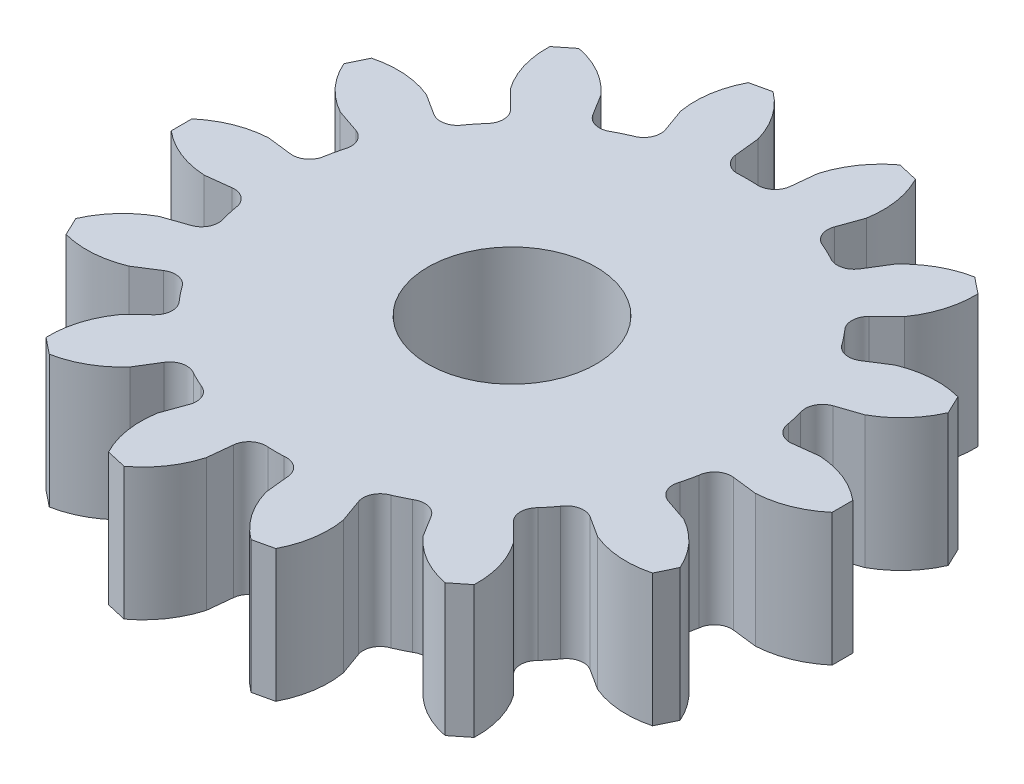
SolidWorks part; units mm, degrees
material "PLA"
ref_plane "Front Plane" through (0, 0, 0) normal (0, 0, 1) x (1, 0, 0)
ref_plane "Top Plane" through (0, 0, 0) normal (0, 1, 0) x (1, 0, 0)
ref_plane "Right Plane" through (0, 0, 0) normal (1, 0, 0) x (0, 0, -1)
sketch "Sketch1" plane through (0, 0, 0) normal (0, 1, 0) x (1, 0, 0)
  line L0 (0, 0) -> (-9.9867, 0) construction
  line L1 (-7.9271, 2.7354) -> (-7.213, 2.4916)
  line L2 (-9.1335, 4.0511) -> (-8.8619, 4.615)
  line L3 (-7.0811, 4.4922) -> (-6.4452, 4.0858)
  line L4 (-5.9552, 5.904) -> (-5.4176, 5.3745)
  line L5 (-6.4713, 7.6128) -> (-5.9819, 8.0031)
  line L6 (-4.4308, 7.1197) -> (-4.0342, 6.4777)
  line L7 (-2.8038, 7.9032) -> (-2.5492, 7.1928)
  line L8 (-2.5274, 9.6667) -> (-1.9171, 9.806)
  line L9 (-0.9029, 8.3371) -> (-0.8241, 7.5866)
  line L10 (0.9029, 8.3371) -> (0.8241, 7.5866)
  line L11 (1.9171, 9.806) -> (2.5274, 9.6667)
  line L12 (2.8038, 7.9032) -> (2.5492, 7.1928)
  line L13 (4.4308, 7.1197) -> (4.0342, 6.4777)
  line L14 (5.9819, 8.0031) -> (6.4713, 7.6128)
  line L15 (5.9552, 5.904) -> (5.4176, 5.3745)
  line L16 (7.0811, 4.4922) -> (6.4452, 4.0858)
  line L17 (-9.9867, -0.313) -> (-9.9867, 0.313)
  line L18 (-9.9867, 0.313) -> (-8.9385, 0.313) construction
  line L19 (-8.9385, 0.313) -> (-8.9385, 0.8733) construction
  line L20 (-8.9385, 0.8733) -> (-8.3289, 0.8733) construction
  line L21 (-8.3289, 0.8733) -> (-8.3289, 0.9749) construction
  line L22 (-8.3289, 0.9749) -> (-7.5797, 0.9749) construction
  line L23 (-7.5797, 0.9749) -> (-7.5797, 0.8847) construction
  line L24 (-8.3289, 0.9749) -> (-7.5797, 0.8847)
  line L25 (-7.5797, 0.8847) -> (-7.5797, 1.3491) construction
  line L26 (-7.5797, 1.3491) -> (-7.0037, 1.3491) construction
  line L27 (-8.3289, -0.9749) -> (-7.5797, -0.8847)
  line L28 (8.8619, 4.615) -> (9.1335, 4.0511)
  line L29 (7.9271, 2.7354) -> (7.213, 2.4916)
  line L30 (8.3289, 0.9749) -> (7.5797, 0.8847)
  line L31 (9.9867, 0.313) -> (9.9867, -0.313)
  line L32 (8.3289, -0.9749) -> (7.5797, -0.8847)
  line L33 (7.9271, -2.7354) -> (7.213, -2.4916)
  line L34 (9.1335, -4.0511) -> (8.8619, -4.615)
  line L35 (7.0811, -4.4922) -> (6.4452, -4.0858)
  line L36 (5.9552, -5.904) -> (5.4176, -5.3745)
  line L37 (6.4713, -7.6128) -> (5.9819, -8.0031)
  line L38 (4.4308, -7.1197) -> (4.0342, -6.4777)
  line L39 (2.8038, -7.9032) -> (2.5492, -7.1928)
  line L40 (2.5274, -9.6667) -> (1.9171, -9.806)
  line L41 (0.9029, -8.3371) -> (0.8241, -7.5866)
  line L42 (-0.9029, -8.3371) -> (-0.8241, -7.5866)
  line L43 (-1.9171, -9.806) -> (-2.5274, -9.6667)
  line L44 (-2.8038, -7.9032) -> (-2.5492, -7.1928)
  line L45 (-4.4308, -7.1197) -> (-4.0342, -6.4777)
  line L46 (-5.9819, -8.0031) -> (-6.4713, -7.6128)
  line L47 (-5.9552, -5.904) -> (-5.4176, -5.3745)
  line L48 (-7.0811, -4.4922) -> (-6.4452, -4.0858)
  line L49 (-8.8619, -4.615) -> (-9.1335, -4.0511)
  line L50 (-7.9271, -2.7354) -> (-7.213, -2.4916)
  line L51 (0, 0) -> (0, 2.54) construction
  arc A122 (-7.0037, -1.3491) -> (-6.8955, -1.8233) centre (0, 0) ccw
  arc A123 (-6.8955, 1.8233) -> (-7.0037, 1.3491) centre (0, 0) ccw
  arc A124 (-7.213, 2.4916) -> (-6.8955, 1.8233) centre (-7.3799, 2.0028) cw
  arc A125 (-9.9867, 0.313) -> (-8.3289, 0.9749) centre (-8.1781, -1.8096) cw
  arc A126 (-7.5797, 0.8847) -> (-7.0037, 1.3491) centre (-7.518, 1.3976) ccw
  arc A127 (-9.1335, 4.0511) -> (-7.9271, 2.7354) centre (-6.5831, 5.1788) ccw
  arc A128 (-7.5797, -0.8847) -> (-7.0037, -1.3491) centre (-7.518, -1.3976) cw
  arc A129 (-9.9867, -0.313) -> (-8.3289, -0.9749) centre (-8.1781, 1.8096) ccw
  arc A130 (-8.8619, 4.615) -> (-7.0811, 4.4922) centre (-8.1534, 1.9179) cw
  arc A131 (-6.4452, 4.0858) -> (-5.7248, 4.2543) centre (-6.1671, 4.5211) ccw
  arc A132 (-5.4215, 4.6346) -> (-5.7248, 4.2543) centre (0, 0) ccw
  arc A133 (-5.4176, 5.3745) -> (-5.4215, 4.6346) centre (-5.78, 5.0065) cw
  arc A134 (-6.4713, 7.6128) -> (-5.9552, 5.904) centre (-3.6842, 7.5222) ccw
  arc A135 (-5.9819, 8.0031) -> (-4.4308, 7.1197) centre (-6.5138, 5.2656) cw
  arc A136 (-4.0342, 6.4777) -> (-3.312, 6.3169) centre (-3.5947, 6.7492) ccw
  arc A137 (-2.8738, 6.5279) -> (-3.312, 6.3169) centre (0, 0) ccw
  arc A138 (-2.5492, 7.1928) -> (-2.8738, 6.5279) centre (-3.0354, 7.0185) cw
  arc A139 (-2.5274, 9.6667) -> (-2.8038, 7.9032) centre (-0.0556, 8.3758) ccw
  arc A140 (-1.9171, 9.806) -> (-0.9029, 8.3371) centre (-3.584, 7.5704) cw
  arc A141 (-0.8241, 7.5866) -> (-0.2432, 7.1284) centre (-0.3104, 7.6405) ccw
  arc A142 (0.2432, 7.1284) -> (-0.2432, 7.1284) centre (0, 0) ccw
  arc A143 (0.8241, 7.5866) -> (0.2432, 7.1284) centre (0.3104, 7.6405) cw
  arc A144 (1.9171, 9.806) -> (0.9029, 8.3371) centre (3.584, 7.5704) ccw
  arc A145 (2.5274, 9.6667) -> (2.8038, 7.9032) centre (0.0556, 8.3758) cw
  arc A146 (2.5492, 7.1928) -> (2.8738, 6.5279) centre (3.0354, 7.0185) ccw
  arc A147 (3.312, 6.3169) -> (2.8738, 6.5279) centre (0, 0) ccw
  arc A148 (4.0342, 6.4777) -> (3.312, 6.3169) centre (3.5947, 6.7492) cw
  arc A149 (5.9819, 8.0031) -> (4.4308, 7.1197) centre (6.5138, 5.2656) ccw
  arc A150 (6.4713, 7.6128) -> (5.9552, 5.904) centre (3.6842, 7.5222) cw
  arc A151 (5.4176, 5.3745) -> (5.4215, 4.6346) centre (5.78, 5.0065) ccw
  arc A152 (5.7248, 4.2543) -> (5.4215, 4.6346) centre (0, 0) ccw
  arc A153 (6.4452, 4.0858) -> (5.7248, 4.2543) centre (6.1671, 4.5211) cw
  arc A154 (8.8619, 4.615) -> (7.0811, 4.4922) centre (8.1534, 1.9179) ccw
  arc A155 (9.1335, 4.0511) -> (7.9271, 2.7354) centre (6.5831, 5.1788) cw
  arc A156 (7.213, 2.4916) -> (6.8955, 1.8233) centre (7.3799, 2.0028) ccw
  arc A157 (7.0037, 1.3491) -> (6.8955, 1.8233) centre (0, 0) ccw
  arc A158 (7.5797, 0.8847) -> (7.0037, 1.3491) centre (7.518, 1.3976) cw
  arc A159 (9.9867, 0.313) -> (8.3289, 0.9749) centre (8.1781, -1.8096) ccw
  arc A160 (9.9867, -0.313) -> (8.3289, -0.9749) centre (8.1781, 1.8096) cw
  arc A161 (7.5797, -0.8847) -> (7.0037, -1.3491) centre (7.518, -1.3976) ccw
  arc A162 (6.8955, -1.8233) -> (7.0037, -1.3491) centre (0, 0) ccw
  arc A163 (7.213, -2.4916) -> (6.8955, -1.8233) centre (7.3799, -2.0028) cw
  arc A164 (9.1335, -4.0511) -> (7.9271, -2.7354) centre (6.5831, -5.1788) ccw
  arc A165 (8.8619, -4.615) -> (7.0811, -4.4922) centre (8.1534, -1.9179) cw
  arc A166 (6.4452, -4.0858) -> (5.7248, -4.2543) centre (6.1671, -4.5211) ccw
  arc A167 (5.4215, -4.6346) -> (5.7248, -4.2543) centre (0, 0) ccw
  arc A168 (5.4176, -5.3745) -> (5.4215, -4.6346) centre (5.78, -5.0065) cw
  arc A169 (6.4713, -7.6128) -> (5.9552, -5.904) centre (3.6842, -7.5222) ccw
  arc A170 (5.9819, -8.0031) -> (4.4308, -7.1197) centre (6.5138, -5.2656) cw
  arc A171 (4.0342, -6.4777) -> (3.312, -6.3169) centre (3.5947, -6.7492) ccw
  arc A172 (2.8738, -6.5279) -> (3.312, -6.3169) centre (0, 0) ccw
  arc A173 (2.5492, -7.1928) -> (2.8738, -6.5279) centre (3.0354, -7.0185) cw
  arc A174 (2.5274, -9.6667) -> (2.8038, -7.9032) centre (0.0556, -8.3758) ccw
  arc A175 (1.9171, -9.806) -> (0.9029, -8.3371) centre (3.584, -7.5704) cw
  arc A176 (0.8241, -7.5866) -> (0.2432, -7.1284) centre (0.3104, -7.6405) ccw
  arc A177 (-0.2432, -7.1284) -> (0.2432, -7.1284) centre (0, 0) ccw
  arc A178 (-0.8241, -7.5866) -> (-0.2432, -7.1284) centre (-0.3104, -7.6405) cw
  arc A179 (-1.9171, -9.806) -> (-0.9029, -8.3371) centre (-3.584, -7.5704) ccw
  arc A180 (-2.5274, -9.6667) -> (-2.8038, -7.9032) centre (-0.0556, -8.3758) cw
  arc A181 (-2.5492, -7.1928) -> (-2.8738, -6.5279) centre (-3.0354, -7.0185) ccw
  arc A182 (-3.312, -6.3169) -> (-2.8738, -6.5279) centre (0, 0) ccw
  arc A183 (-4.0342, -6.4777) -> (-3.312, -6.3169) centre (-3.5947, -6.7492) cw
  arc A184 (-5.9819, -8.0031) -> (-4.4308, -7.1197) centre (-6.5138, -5.2656) ccw
  arc A185 (-6.4713, -7.6128) -> (-5.9552, -5.904) centre (-3.6842, -7.5222) cw
  arc A186 (-5.4176, -5.3745) -> (-5.4215, -4.6346) centre (-5.78, -5.0065) ccw
  arc A187 (-5.7248, -4.2543) -> (-5.4215, -4.6346) centre (0, 0) ccw
  arc A188 (-6.4452, -4.0858) -> (-5.7248, -4.2543) centre (-6.1671, -4.5211) cw
  arc A189 (-8.8619, -4.615) -> (-7.0811, -4.4922) centre (-8.1534, -1.9179) ccw
  arc A190 (-9.1335, -4.0511) -> (-7.9271, -2.7354) centre (-6.5831, -5.1788) cw
  arc A191 (-7.213, -2.4916) -> (-6.8955, -1.8233) centre (-7.3799, -2.0028) ccw
  circle A194 centre (0, 0) radius 2.5424
  point P99 (-9.9911, 0)
  dimension "D20" = 0.5603
  dimension "D21" = 1.0482
  dimension "D22" = 0.1016
  dimension "D23" = 0.6096
  dimension "D24" = 0.0902
extrude "Boss-Extrude1" add sketch "Sketch1" along normal blind 4
sketch "Sketch2" plane through (0, 4, 0) normal (0, 1, 0) x (1, 0, 0)
  circle A0 centre (0, 0) radius 8.3858 construction
  circle A1 centre (0, 0) radius 2.5424 construction
  point P3 (0, 0)
  point P4 (0, 0)
sketch "Sketch3" plane through (0, 4, 0) normal (0, 1, 0) x (1, 0, 0)
  line L0 (0.5625, 7.1303) -> (-0.5625, 7.1303) construction
  point P0 (0, 7.1303)
